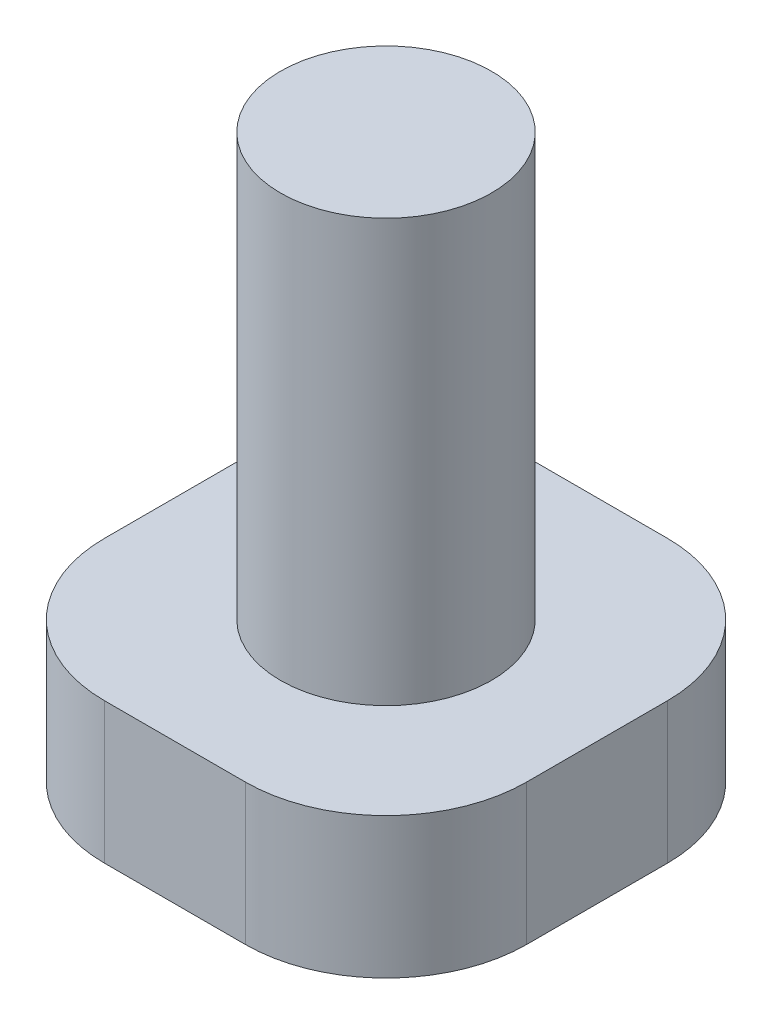
SolidWorks part; units mm, degrees
ref_plane "Front Plane" through (0, 0, 0) normal (0, 0, 1) x (1, 0, 0)
ref_plane "Top Plane" through (0, 0, 0) normal (0, 1, 0) x (1, 0, 0)
ref_plane "Right Plane" through (0, 0, 0) normal (1, 0, 0) x (0, 0, -1)
sketch "Sketch1" plane through (0, 0, 0) normal (0, 1, 0) x (1, 0, 0)
  line L1 (0, 0) -> (7.62, 0)
  line L2 (0, 0) -> (0, 7.62)
  line L3 (0, 7.62) -> (7.62, 7.62)
  line L4 (7.62, 0) -> (7.62, 7.62)
  dimension "D1" = 7.62
  dimension "D2" = 7.62
extrude "Boss-Extrude1" add sketch "Sketch1" along normal blind 10.16
sketch "Sketch2" plane through (0, 10.16, 0) normal (0, 1, 0) x (1, 0, 0)
  line L1 (0, 7.62) -> (7.62, 7.62)
  line L2 (0, 7.62) -> (0, 0)
  line L3 (0, 0) -> (7.62, 0)
  line L4 (7.62, 7.62) -> (7.62, 0)
  circle A0 centre (3.81, 3.81) radius 1.905
  dimension "D1" = 3.81
extrude "Cut-Extrude1" cut sketch "Sketch2" against normal blind 7.62
fillet "Fillet1" radius 2.54 1 edges at (7.62, 1.27, -7.62)
fillet "Fillet2" radius 2.54 1 edges at (0, 1.27, -7.62)
fillet "Fillet3" radius 2.54 1 edges at (7.62, 1.27, 0)
fillet "Fillet4" radius 2.54 1 edges at (0, 1.27, 0)
